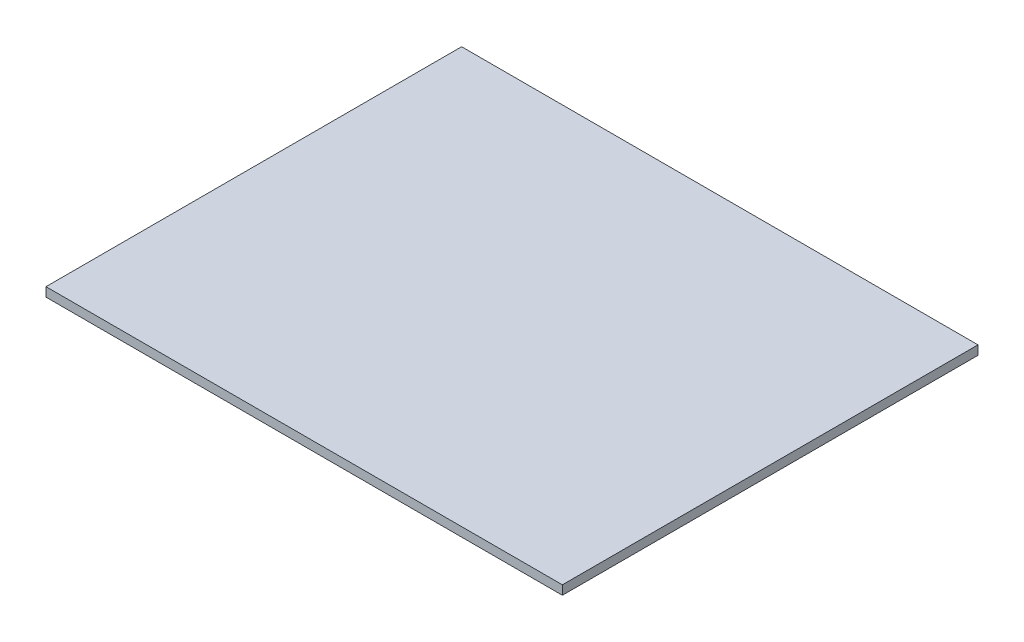
SolidWorks part; units mm, degrees
ref_plane "Front Plane" through (0, 0, 0) normal (0, 0, 1) x (1, 0, 0)
ref_plane "Top Plane" through (0, 0, 0) normal (0, 1, 0) x (1, 0, 0)
ref_plane "Right Plane" through (0, 0, 0) normal (1, 0, 0) x (0, 0, -1)
sketch "Sketch1" plane through (0, 0, 0) normal (0, 1, 0) x (1, 0, 0)
  line L1 (-123, 99) -> (123, 99)
  line L2 (-123, 99) -> (-123, -99)
  line L3 (-123, -99) -> (123, -99)
  line L4 (123, 99) -> (123, -99)
  line L5 (-123, 99) -> (123, -99) construction
  line L6 (-123, -99) -> (123, 99) construction
  point P0 (0, 0)
  dimension "D1" = 246
  dimension "D2" = 198
extrude "Boss-Extrude1" add sketch "Sketch1" along normal blind 4.33
